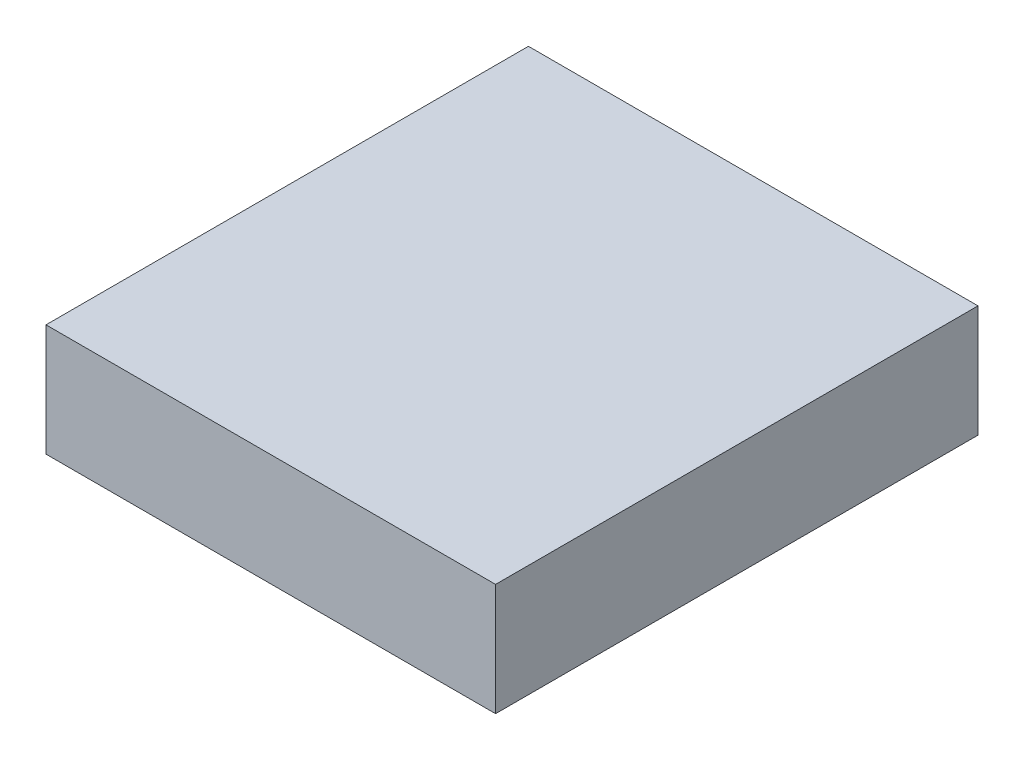
SolidWorks part; units mm, degrees
ref_plane "Front Plane" through (0, 0, 0) normal (0, 0, 1) x (1, 0, 0)
ref_plane "Top Plane" through (0, 0, 0) normal (0, 1, 0) x (1, 0, 0)
ref_plane "Right Plane" through (0, 0, 0) normal (1, 0, 0) x (0, 0, -1)
sketch "Sketch1" plane through (0, 0, 0) normal (0, 0, 1) x (1, 0, 0)
  line L1 (0, 0) -> (93.1875, 0)
  line L2 (0, 0) -> (0, 23.216)
  line L3 (0, 23.216) -> (93.1875, 23.216)
  line L4 (93.1875, 0) -> (93.1875, 23.216)
extrude "Boss-Extrude1" add sketch "Sketch1" along normal blind 100
